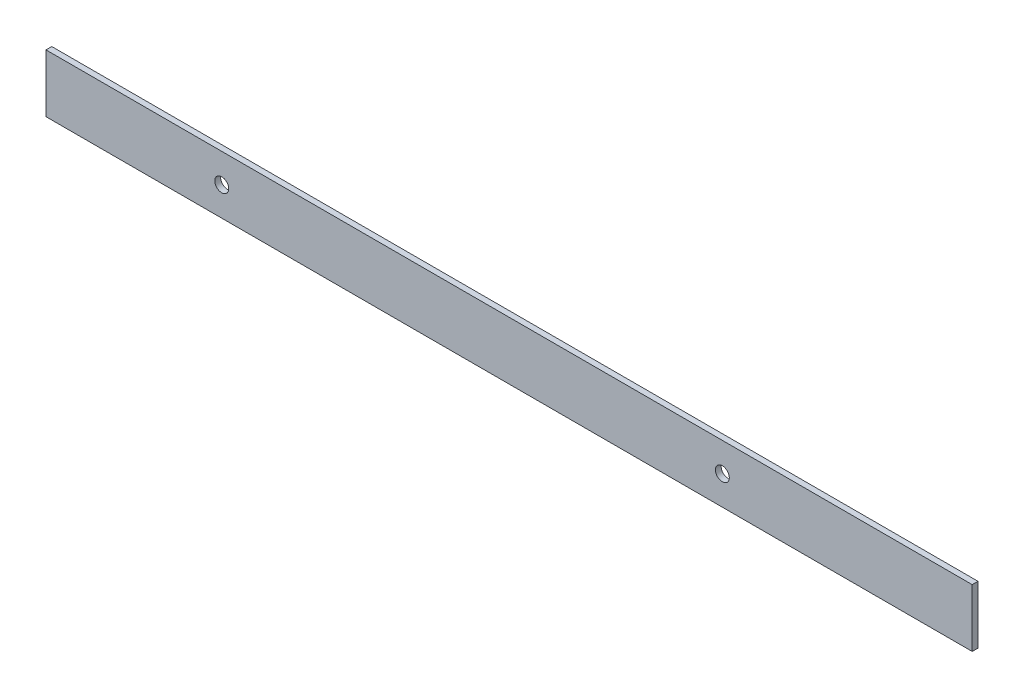
SolidWorks part; units mm, degrees
ref_plane "Płaszczyzna przednia" through (0, 0, 0) normal (0, 0, 1) x (1, 0, 0)
ref_plane "Płaszczyzna górna" through (0, 0, 0) normal (0, 1, 0) x (1, 0, 0)
ref_plane "Płaszczyzna prawa" through (0, 0, 0) normal (1, 0, 0) x (0, 0, -1)
sketch "Szkic1" plane through (0, 0, 0) normal (0, 0, 1) x (1, 0, 0)
  line L0 (400, 0) -> (400, 50)
  line L1 (0, 0) -> (800, 0)
  line L2 (0, 0) -> (0, 50)
  line L3 (0, 50) -> (800, 50)
  line L4 (800, 0) -> (800, 50)
  circle A0 centre (151.7988, 25.0027) radius 6
  circle A1 centre (584.1763, 25.0027) radius 6
  dimension "D5" = 12
  dimension "D6" = 12
  dimension "D1" = 800
  dimension "D2" = 50
extrude "Dodanie-wyciągnięcie1" add sketch "Szkic1" along normal blind 5 contours L3 L2 L1 L0 A0 | L1 L4 L3 L0 A1
